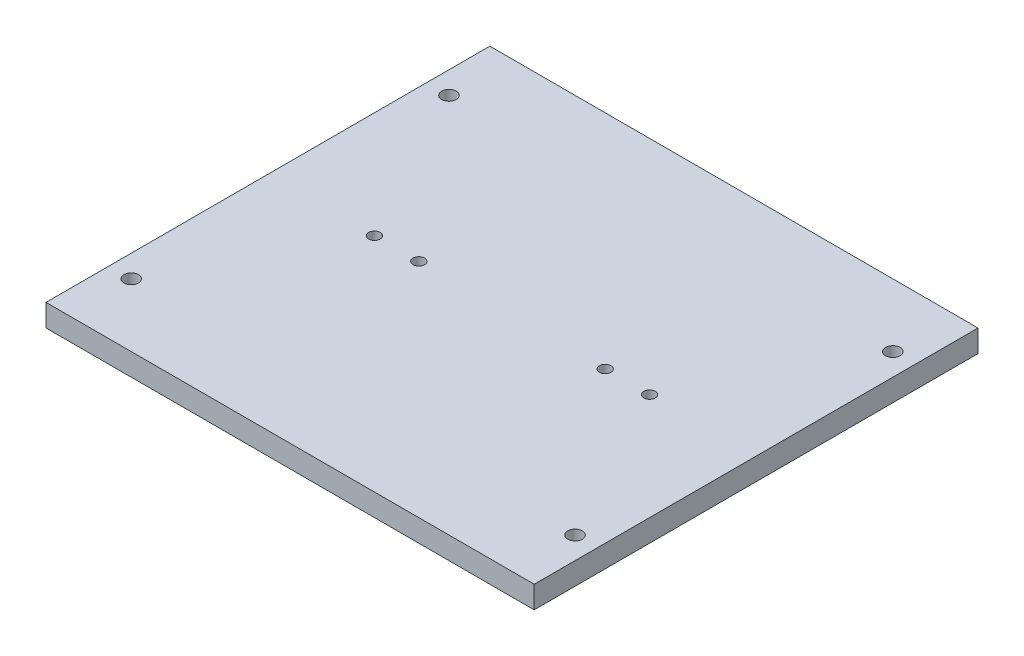
SolidWorks part; units mm, degrees
ref_plane "Front Plane" through (0, 0, 0) normal (0, 0, 1) x (1, 0, 0)
ref_plane "Top Plane" through (0, 0, 0) normal (0, 1, 0) x (1, 0, 0)
ref_plane "Right Plane" through (0, 0, 0) normal (1, 0, 0) x (0, 0, -1)
sketch "Sketch1" plane through (0, 0, 0) normal (0, 1, 0) x (1, 0, 0)
  line L0 (0, 190.5) -> (139.7, 190.5)
  line L2 (139.7, 190.5) -> (139.7, 63.5)
  line L3 (69.85, 190.5) -> (69.85, 63.5) construction
  line L4 (139.7, 63.5) -> (0, 63.5)
  line L5 (0, 127) -> (152.4, 127) construction
  line L6 (139.7, 127) -> (146.05, 127) construction
  line L7 (133.35, 190.5) -> (133.35, 172.466) construction
  line L8 (133.35, 63.5) -> (133.35, 81.534) construction
  line L9 (6.35, 190.5) -> (6.35, 172.466) construction
  line L10 (6.35, 63.5) -> (6.35, 81.534) construction
  line L11 (69.85, 63.5) -> (69.85, 76.2) construction
  line L12 (146.05, 127) -> (69.85, 127) construction
  line L13 (69.85, 63.5) -> (69.85, 127) construction
  line L14 (139.7, 127) -> (134.62, 127) construction
  line L15 (5.08, 127) -> (17.78, 127) construction
  line L16 (0, 63.5) -> (0, 190.5)
  line L17 (0, 127) -> (5.08, 127) construction
  circle A0 centre (133.35, 172.466) radius 2.0828
  circle A1 centre (133.35, 81.534) radius 2.0828
  circle A2 centre (6.35, 172.466) radius 2.0828
  circle A3 centre (6.35, 81.534) radius 2.0828
  circle A5 centre (43.18, 127) radius 1.651
  circle A7 centre (109.22, 127) radius 1.651
  circle A8 centre (96.52, 127) radius 1.651
  circle A9 centre (30.48, 127) radius 1.651
  dimension "D1" = 139.7
  dimension "D3" = 18.034
  dimension "D5" = 12.7
  dimension "D2" = 127
  dimension "D4" = 30.48
  dimension "D6" = 63.5
extrude "Boss-Extrude1" add sketch "Sketch1" along normal blind 6.35
